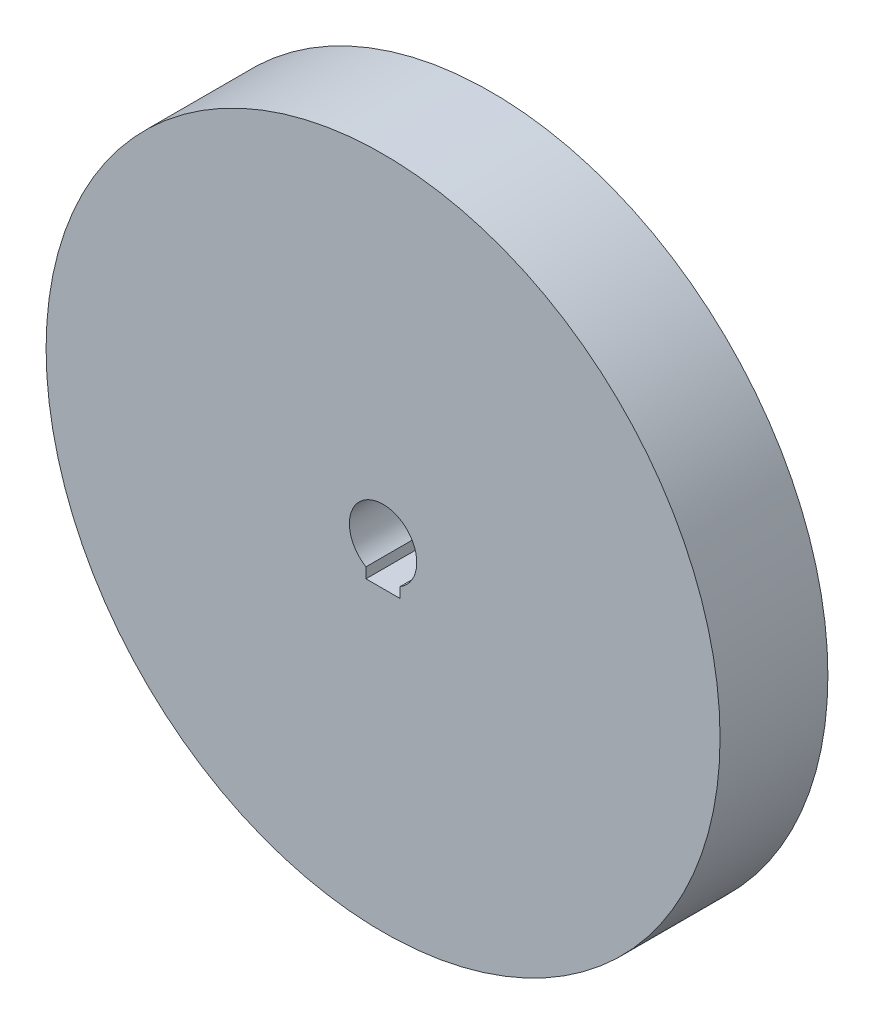
SolidWorks part; units mm, degrees
ref_plane "Front Plane" through (0, 0, 0) normal (0, 0, 1) x (1, 0, 0)
ref_plane "Top Plane" through (0, 0, 0) normal (0, 1, 0) x (1, 0, 0)
ref_plane "Right Plane" through (0, 0, 0) normal (1, 0, 0) x (0, 0, -1)
sketch "Sketch1" plane through (0, 0, 0) normal (0, 0, 1) x (1, 0, 0)
  circle A0 centre (0, 0) radius 12.5
  circle A1 centre (0, 0) radius 125
  dimension "D1" = 25
  dimension "D2" = 250
extrude "Boss-Extrude1" add sketch "Sketch1" along normal blind 40
sketch "Sketch2" plane through (0, 0, 40) normal (0, 0, 1) x (1, 0, 0)
  line L1 (-6.341, -14.6346) -> (6.341, -14.6346)
  line L2 (-6.341, -14.6346) -> (-6.341, -8.9601)
  line L3 (-6.341, -8.9601) -> (6.341, -8.9601)
  line L4 (6.341, -14.6346) -> (6.341, -8.9601)
  line L5 (-6.341, -14.6346) -> (6.341, -8.9601) construction
  line L6 (-6.341, -8.9601) -> (6.341, -14.6346) construction
  point P0 (0, -11.7974)
  point P5 (0, 0)
extrude "Cut-Extrude1" cut sketch "Sketch2" against normal up to body
